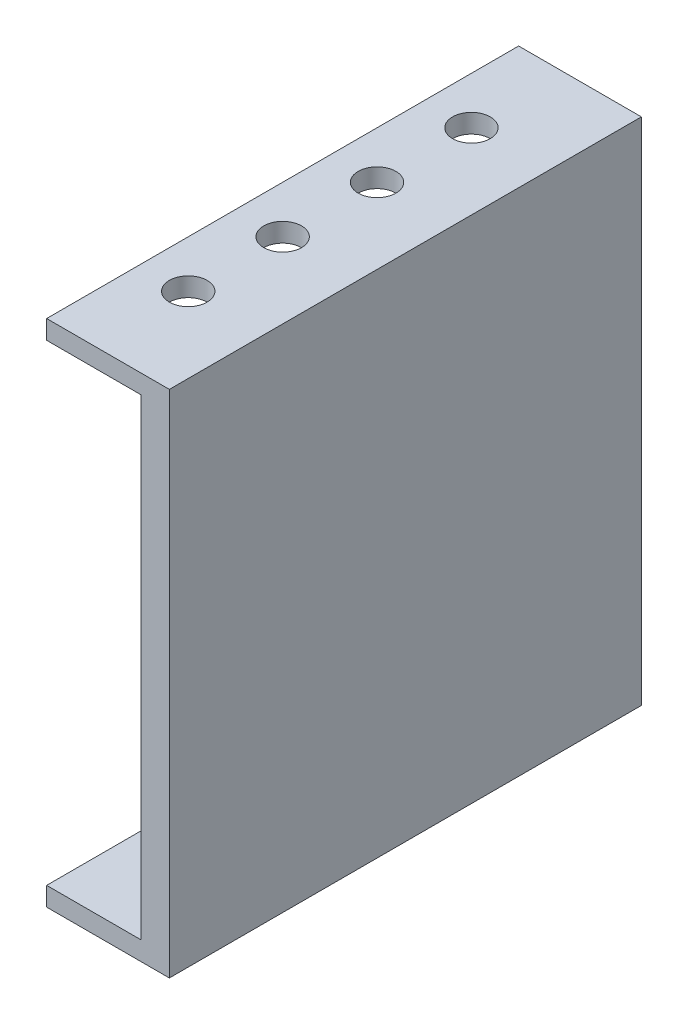
SolidWorks part; units mm, degrees
material "AISI 304"
ref_plane "前视基准面" through (0, 0, 0) normal (0, 0, 1) x (1, 0, 0)
ref_plane "上视基准面" through (0, 0, 0) normal (0, 1, 0) x (1, 0, 0)
ref_plane "右视基准面" through (0, 0, 0) normal (1, 0, 0) x (0, 0, -1)
sketch "草图1" plane through (0, 0, 0) normal (0, 1, 0) x (1, 0, 0)
  line L1 (-5, 25) -> (5, 25)
  line L2 (-5, 25) -> (-5, -25)
  line L3 (-5, -25) -> (5, -25)
  line L4 (5, 25) -> (5, -25)
  line L5 (-5, 25) -> (5, -25) construction
  line L6 (-5, -25) -> (5, 25) construction
  point P0 (0, 0)
  dimension "D1" = 10
  dimension "D2" = 50
extrude "凸台-拉伸1" add sketch "草图1" along normal blind 2
sketch "草图2" plane through (5, 0, 0) normal (1, 0, 0) x (0, 0, -1)
  line L4 (-25, 0) -> (25, 0)
  line L5 (25, 0) -> (25, 2)
  line L6 (25, 2) -> (-25, 2)
  line L7 (-25, 2) -> (-25, 0)
  line L8 (-25, 0) -> (25, 0)
  line L9 (25, 0) -> (25, 2)
  line L10 (25, 2) -> (-25, 2)
  line L11 (-25, 2) -> (-25, 0)
  dimension "D1" = 0
extrude "凸台-拉伸2" add sketch "草图2" along normal blind 3
sketch "草图3" plane through (0, 0, 0) normal (0, -1, 0) x (1, 0, 0)
  line L0 (5, -25) -> (5, 25)
  line L1 (8, -25) -> (-5, -25) construction
  line L2 (-5, 25) -> (8, 25) construction
  line L3 (5, 25) -> (8, 25)
  line L4 (8, 25) -> (8, -25)
  line L5 (8, -25) -> (5, -25)
  dimension "D1" = 3
extrude "凸台-拉伸3" add sketch "草图3" along normal blind 52
sketch "草图4" plane through (5, 0, 0) normal (-1, 0, 0) x (0, 0, 1)
  line L0 (-25, -50) -> (25, -50)
  line L1 (-25, -52) -> (-25, 0) construction
  line L2 (25, -52) -> (25, 0) construction
  line L3 (25, -50) -> (25, -52)
  line L4 (25, -52) -> (-25, -52)
  line L5 (25, -52) -> (-25, -52) construction
  line L6 (-25, -52) -> (-25, -50)
  dimension "D1" = 2
extrude "凸台-拉伸4" add sketch "草图4" along normal blind 10
sketch "草图5" plane through (0, -52, 0) normal (0, -1, 0) x (-1, 0, 0)
  line L0 (-1.5, 25) -> (-1.5, -25) construction
  line L1 (5, 25) -> (-8, 25) construction
  line L2 (-8, -25) -> (5, -25) construction
  circle A0 centre (-1.5, -15) radius 2
  circle A1 centre (-1.5, -5) radius 2
  circle A2 centre (-1.5, 5) radius 2
  circle A3 centre (-1.5, 15) radius 2
  dimension "D1" = 4
  dimension "D2" = 10
  dimension "D3" = 4
extrude "切除-拉伸1" cut sketch "草图5" against normal through all
sketch "草图6" plane through (8, 0, 0) normal (1, 0, 0) x (0, 0, -1)
  line L4 (-25, 2) -> (-25, -52)
  line L5 (-25, -52) -> (25, -52)
  line L6 (25, -52) -> (25, 2)
  line L7 (25, 2) -> (-25, 2)
  line L8 (-25, 2) -> (-25, -52)
  line L9 (-25, -52) -> (25, -52)
  line L10 (25, -52) -> (25, 2)
  line L11 (25, 2) -> (-25, 2)
  dimension "D1" = 0
extrude "凸台-拉伸5" add sketch "草图6" along normal blind 1.5
sketch "草图7" plane through (5, 0, 0) normal (-1, 0, 0) x (0, 0, 1)
  line L4 (-25, -50) -> (25, -50)
  line L5 (25, -50) -> (25, 0)
  line L6 (25, 0) -> (-25, 0)
  line L9 (25, -50) -> (25, 0)
  line L10 (25, 0) -> (-25, 0)
  line L12 (-25, -50) -> (25, -50)
  line L14 (-25, 0) -> (-25, -50)
  line L15 (-25, 0) -> (-25, -50)
  dimension "D1" = 0
extrude "切除-拉伸2" cut sketch "草图7" against normal blind 1.5
sketch "草图8" plane through (-5, 0, 0) normal (-1, 0, 0) x (0, 0, 1)
  line L4 (-25, -50) -> (-25, -52)
  line L5 (-25, -52) -> (25, -52)
  line L6 (25, -52) -> (25, -50)
  line L7 (25, -50) -> (-25, -50)
  line L8 (-25, -50) -> (-25, -52)
  line L9 (-25, -52) -> (25, -52)
  line L10 (25, -52) -> (25, -50)
  line L11 (25, -50) -> (-25, -50)
  line L12 (-25, 0) -> (25, 0)
  line L13 (25, 0) -> (25, 2)
  line L14 (25, 2) -> (-25, 2)
  line L15 (-25, 2) -> (-25, 0)
  line L16 (-25, 0) -> (25, 0)
  line L17 (25, 0) -> (25, 2)
  line L18 (25, 2) -> (-25, 2)
  line L19 (-25, 2) -> (-25, 0)
  dimension "D1" = 0
  dimension "D2" = 0
extrude "切除-拉伸3" cut sketch "草图8" against normal blind 1.5
